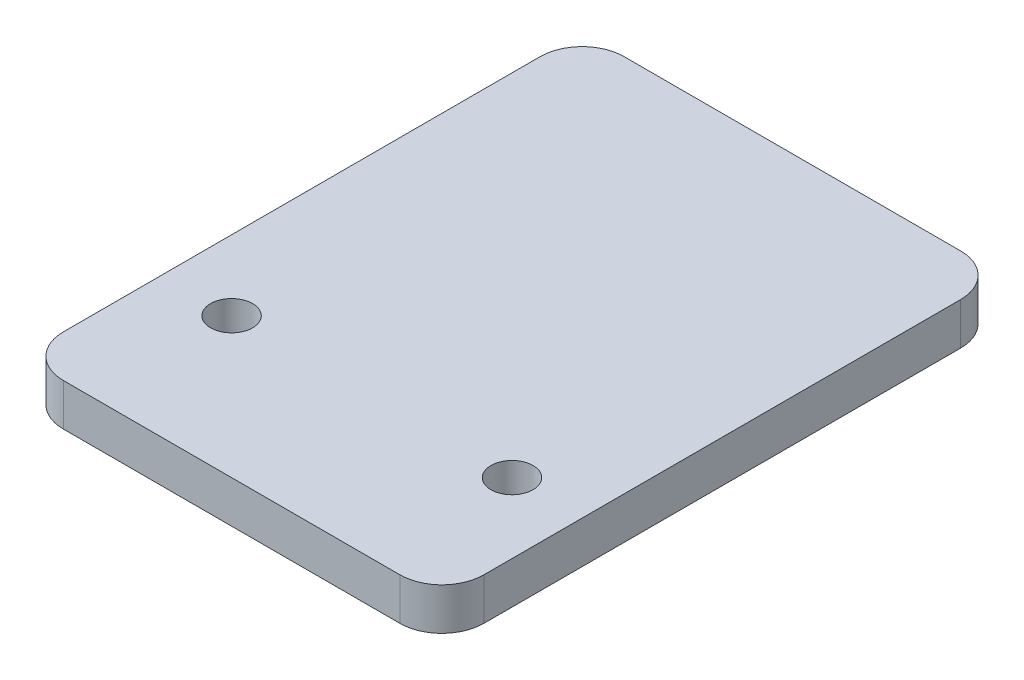
SolidWorks part; units mm, degrees
material "Thornel Mat VMA"
ref_plane "前视基准面" through (0, 0, 0) normal (0, 0, 1) x (1, 0, 0)
ref_plane "上视基准面" through (0, 0, 0) normal (0, 1, 0) x (1, 0, 0)
ref_plane "右视基准面" through (0, 0, 0) normal (1, 0, 0) x (0, 0, -1)
sketch "草图1" plane through (0, 0, 0) normal (0, 1, 0) x (1, 0, 0)
  line L1 (-15, -20) -> (15, -20)
  line L2 (-15, -20) -> (-15, 20)
  line L3 (-15, 20) -> (15, 20)
  line L4 (15, -20) -> (15, 20)
  line L5 (-15, -20) -> (15, 20) construction
  line L6 (-15, 20) -> (15, -20) construction
  point P0 (0, 0)
  dimension "D1" = 30
  dimension "D2" = 40
extrude "凸台-拉伸1" add sketch "草图1" along normal blind 3
sketch "草图2" plane through (0, 3, 0) normal (0, 1, 0) x (1, 0, 0)
  line L0 (0, 20) -> (0, -20) construction
  line L1 (15, 20) -> (-15, 20) construction
  line L2 (-15, -20) -> (15, -20) construction
  circle A0 centre (-10, -10) radius 1.5
  circle A1 centre (10, -10) radius 1.5
  dimension "D1" = 10
  dimension "D2" = 10
  dimension "D3" = 3
extrude "切除-拉伸1" cut sketch "草图2" against normal through all
fillet "圆角1" radius 3 4 edges at (15, 1.5, 20) (-15, 1.5, 20) (15, 1.5, -20) (-15, 1.5, -20)
